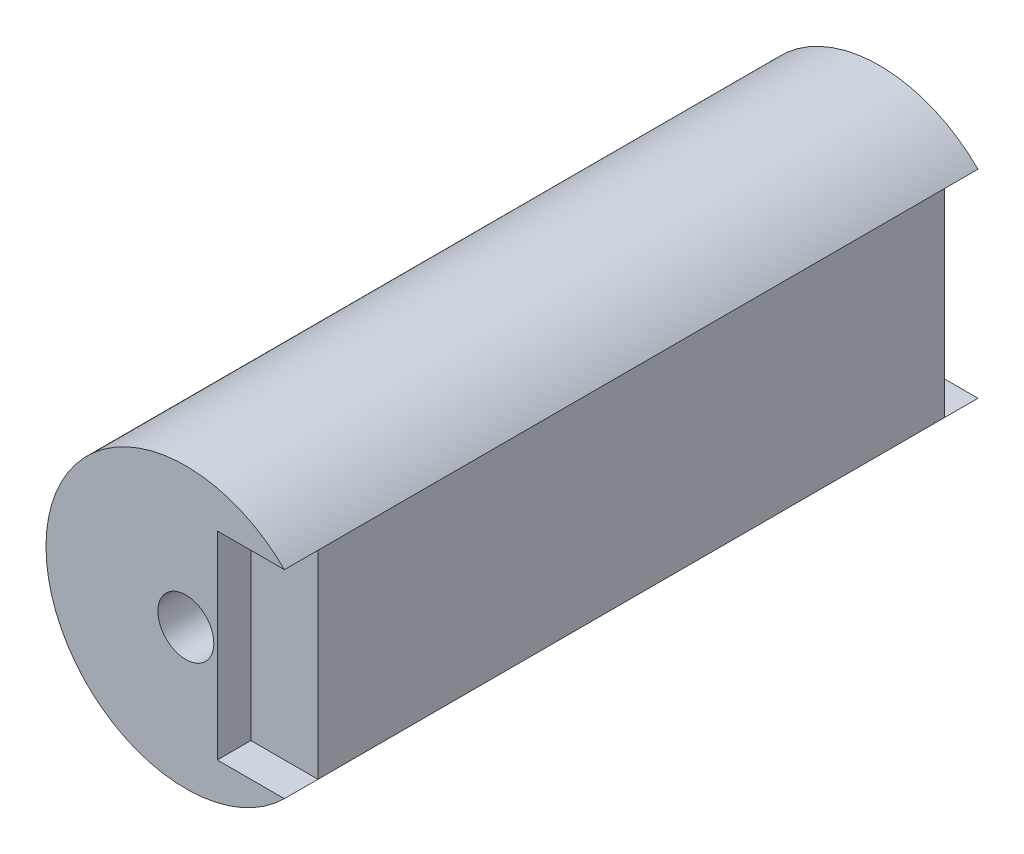
SolidWorks part; units mm, degrees
ref_plane "前视基准面" through (0, 0, 0) normal (0, 0, 1) x (1, 0, 0)
ref_plane "上视基准面" through (0, 0, 0) normal (0, 1, 0) x (1, 0, 0)
ref_plane "右视基准面" through (0, 0, 0) normal (1, 0, 0) x (0, 0, -1)
other "Configuration Table"
sketch "草图1" plane through (0, 0, 0) normal (0, 0, 1) x (1, 0, 0)
  circle A0 centre (0, 0) radius 2.5
  dimension "D1" = 5
extrude "凸台-拉伸1" add sketch "草图1" along normal blind 88.2
cosmetic thread "装饰螺纹线1" parameters "D1"=6.6, "D2"=4
ref_plane "基准面1" through (0, 0, 73.2) normal (0, 0, 1) x (1, 0, 0)
sketch "草图2" plane through (0, 0, 73.2) normal (0, 0, 1) x (1, 0, 0)
  circle A0 centre (0, 0) radius 12.5
  dimension "D1" = 25
extrude "凸台-拉伸2" add sketch "草图2" against normal blind 62
ref_plane "基准面2" through (0, 0, 73.2) normal (0, 0, 1) x (1, 0, 0)
sketch "草图3" plane through (0, 0, 73.2) normal (0, 0, 1) x (1, 0, 0)
  line L4 (0, 8.8652) -> (0, -8.8652)
  line L5 (0, -8.8652) -> (40, -8.8652)
  line L6 (40, -8.8652) -> (40, 8.8652)
  line L7 (40, 8.8652) -> (0, 8.8652)
  line L8 (-12.5, 0) -> (19.0607, 0) construction
  circle A1 centre (0, 0) radius 12.5 construction
  circle A2 centre (32.64, 0) radius 5
  dimension "D2" = 10
  dimension "D1" = 40
extrude "凸台-拉伸3" add sketch "草图3" against normal blind 3
cosmetic thread "装饰螺纹线2" parameters "D2"=11
pattern_linear "阵列(线性)1" count 2 spacing 59 along (0, 0, -1) of "凸台-拉伸3"
sketch "草图4" plane through (0, 0, 73.2) normal (0, 0, 1) x (1, 0, 0)
  line L0 (0, 0) -> (0, 12.3344)
  line L1 (32.64, 0) -> (32.64, 15.3929)
sketch "草图6" plane through (0, 0, 73.2) normal (0, 0, 1) x (1, 0, 0)
  line L1 (8.8124, 8.8652) -> (8.8124, -8.8652)
  line L2 (8.8124, -8.8652) -> (40, -8.8652)
  line L3 (40, -8.8652) -> (40, 8.8652)
  line L4 (40, 8.8652) -> (8.8124, 8.8652)
extrude "切除-拉伸1" cut sketch "草图6" against normal through all both and the other way through all
ref_plane "基准面3" through (8.8124, 0, 0) normal (1, 0, 0) x (0, 0, -1)
sketch "草图8" plane through (8.8124, 0, 0) normal (1, 0, 0) x (0, 0, -1)
  line L0 (-72.621, 8.8652) -> (-74.329, 8.8652)
  line L1 (-11.2, 8.8652) -> (-73.2, 8.8652) construction
  line L2 (-73.2, 10.1254) -> (-73.2, 6.3678)
  line L3 (-73.2, 0) -> (-73.2, 12.3344) construction
  line L4 (-73.2, -8.8652) -> (-11.2, -8.8652) construction
  line L5 (-73.2, 8.8652) -> (-70.2, 8.8652)
  line L6 (-73.2, 8.8652) -> (-73.2, -8.8652)
  line L7 (-73.2, -8.8652) -> (-70.2, -8.8652)
  line L8 (-70.2, 8.8652) -> (-70.2, -8.8652)
  line M4 (-11.2, 8.8652) -> (-73.2, 8.8652)
  line M5 (-73.2, 8.8652) -> (-73.2, -8.8652)
  line M6 (-73.2, -8.8652) -> (-11.2, -8.8652)
  dimension "D1" = 3
extrude "切除-拉伸7" cut sketch "草图8" against normal blind 6 contours L8 M4 M5 M6
pattern_linear "阵列(线性)3" count 2 spacing 59 along (0, 0, -1) of "切除-拉伸7"
sketch "草图9" plane through (8.8124, 0, 0) normal (1, 0, 0) x (0, 0, -1)
  line L0 (-73.2, -2.5313) -> (-73.2, 2.5286)
  line L1 (-73.2, 11.7218) -> (-73.2, -11.7218) construction
  line L2 (-73.2, 0) -> (-73.2, 12.3344) construction
  line L3 (-73.2, 2.5286) -> (-88.2, 2.5)
  line L4 (-88.2, 2.5) -> (-88.2, -2.5)
  line L5 (-88.2, 2.5) -> (-88.2, -2.5) construction
  line L6 (-88.2, -2.5) -> (-73.2, -2.5313)
extrude "切除-拉伸8" cut sketch "草图9" against normal through all
sketch "草图10" plane through (8.8124, 0, 0) normal (1, 0, 0) x (0, 0, -1)
  line L0 (-11.2, 2.5) -> (-11.2, -2.5)
  line L1 (0, 2.5) -> (-11.2, 2.5) construction
  line L2 (-11.2, -2.5) -> (0, -2.5)
  line L3 (0, -2.5) -> (0, 2.5)
  line L4 (0, 2.5) -> (-11.2, 2.5)
extrude "切除-拉伸9" cut sketch "草图10" against normal through all
sketch "草图11" plane through (0, 0, 73.2) normal (0, 0, 1) x (1, 0, 0)
  circle A0 centre (0, 0) radius 2.5
  dimension "D1" = 5
extrude "切除-拉伸10" cut sketch "草图11" against normal through all
cosmetic thread "装饰螺纹线3" parameters "D1"=5, "D2"=6
